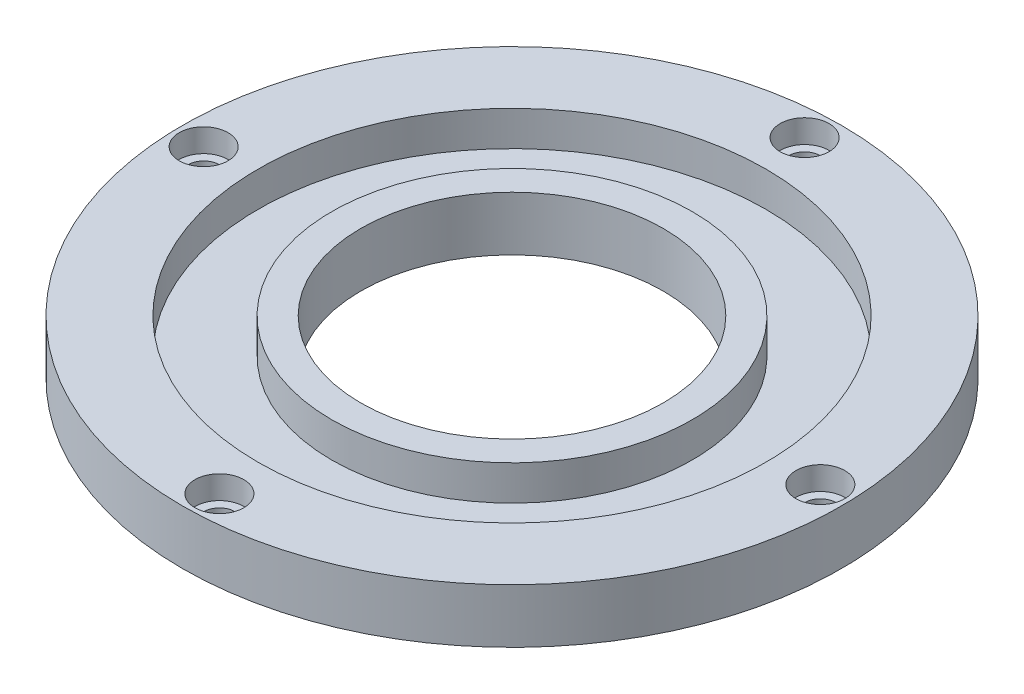
SolidWorks part; units mm, degrees
ref_plane "Ön Düzlem" through (0, 0, 0) normal (0, 0, 1) x (1, 0, 0)
ref_plane "Üst Düzlem" through (0, 0, 0) normal (0, 1, 0) x (1, 0, 0)
ref_plane "Sağ Düzlem" through (0, 0, 0) normal (1, 0, 0) x (0, 0, -1)
sketch "Sketch1" plane through (0, 0, 0) normal (0, 1, 0) x (1, 0, 0)
  circle A0 centre (0, 0) radius 19.5
  circle A1 centre (0, 0) radius 42.5
  dimension "D1" = 39
  dimension "D2" = 85
extrude "Boss-Extrude1" add sketch "Sketch1" along normal blind 7
sketch "Sketch2" plane through (0, 7, 0) normal (0, 1, 0) x (1, 0, 0)
  circle A0 centre (0, 0) radius 32.75
  circle A1 centre (0, 0) radius 23.25
  dimension "D1" = 46.5
  dimension "D2" = 65.5
extrude "Cut-Extrude1" cut sketch "Sketch2" against normal blind 4.5
sketch "Sketch3" plane through (0, 7, 0) normal (0, 1, 0) x (1, 0, 0)
  circle A0 centre (-38.75, -1.0154) radius 2
  circle A1 centre (-1.0154, 38.75) radius 2
  circle A2 centre (38.75, 1.0154) radius 2
  circle A3 centre (1.0154, -38.75) radius 2
  dimension "D1" = 38.75
  dimension "D2" = 4
extrude "Cut-Extrude2" cut sketch "Sketch3" against normal through all
sketch "Sketch4" plane through (0, 7, 0) normal (0, 1, 0) x (1, 0, 0)
  circle A0 centre (-1.0154, 38.75) radius 2 construction
  circle A1 centre (-1.0154, 38.75) radius 2
  circle A2 centre (-1.0154, 38.75) radius 3.15
  circle A3 centre (38.75, 1.0154) radius 3.15
  circle A4 centre (1.0154, -38.75) radius 3.15
  circle A5 centre (-38.75, -1.0154) radius 3.15
  dimension "D1" = 6.3
  dimension "D2" = 4
extrude "Cut-Extrude3" cut sketch "Sketch4" against normal blind 3
